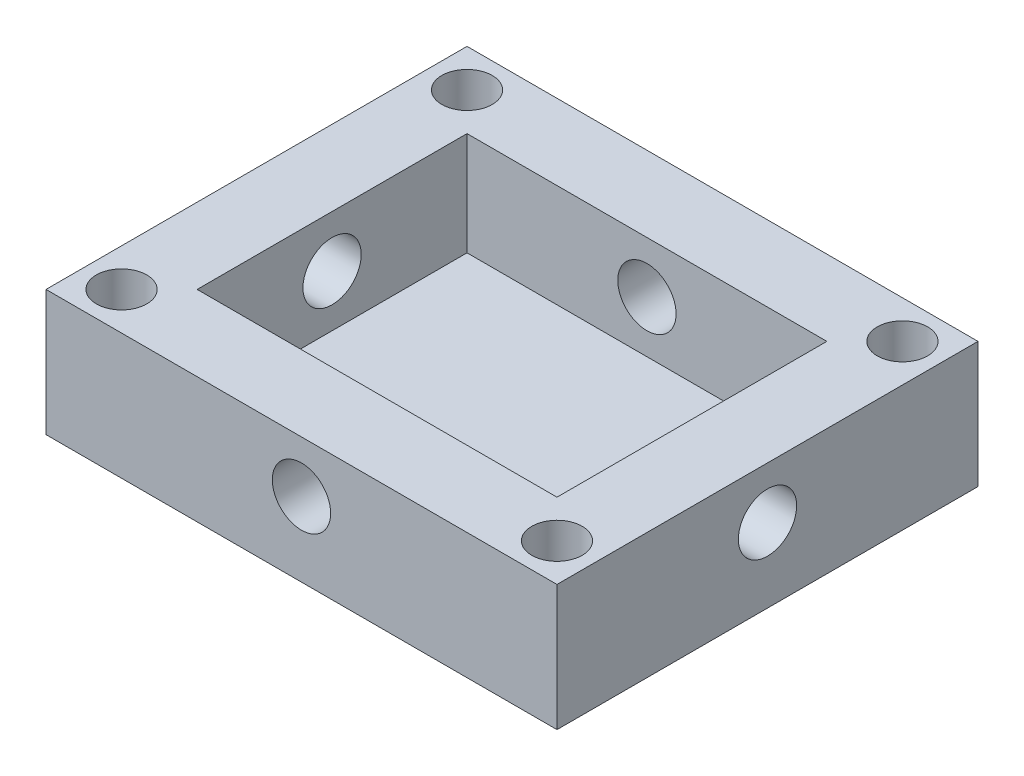
SolidWorks part; units mm, degrees
ref_plane "Front Plane" through (0, 0, 0) normal (0, 0, 1) x (1, 0, 0)
ref_plane "Top Plane" through (0, 0, 0) normal (0, 1, 0) x (1, 0, 0)
ref_plane "Right Plane" through (0, 0, 0) normal (1, 0, 0) x (0, 0, -1)
sketch "Sketch1" plane through (0, 0, 0) normal (0, 1, 0) x (1, 0, 0)
  line L0 (-18.034, 14.859) -> (18.034, 14.859)
  line L1 (-12.7, -9.525) -> (12.7, -9.525)
  line L2 (-12.7, -9.525) -> (-12.7, 9.525)
  line L3 (-12.7, 9.525) -> (12.7, 9.525)
  line L4 (12.7, -9.525) -> (12.7, 9.525)
  line L5 (-12.7, -9.525) -> (12.7, 9.525) construction
  line L6 (-12.7, 9.525) -> (12.7, -9.525) construction
  line L7 (18.034, -14.859) -> (18.034, 14.859)
  line L8 (-18.034, -14.859) -> (18.034, -14.859)
  line L9 (-18.034, -14.859) -> (-18.034, 14.859)
  point P0 (0, 0)
  dimension "D1" = 25.4
  dimension "D2" = 19.05
  dimension "D3" = 5.334
extrude "Boss-Extrude3" add sketch "Sketch1" along normal blind 7.2898
sketch "Sketch4" plane through (0, 0, 0) normal (0, -1, 0) x (1, 0, 0)
  line L1 (-18.034, -14.859) -> (18.034, -14.859)
  line L2 (-18.034, -14.859) -> (-18.034, 14.859)
  line L15 (-18.034, 14.859) -> (18.034, 14.859)
  line L16 (18.034, -14.859) -> (18.034, 14.859)
  line L17 (-18.034, -14.859) -> (18.034, 14.859) construction
  line L18 (-18.034, 14.859) -> (18.034, -14.859) construction
  point P0 (0, 0)
extrude "Boss-Extrude4" add sketch "Sketch4" along normal blind 1.5875
sketch "Sketch5" plane through (0, 7.2898, 0) normal (0, 1, 0) x (1, 0, 0)
  circle A0 centre (-15.367, 12.192) radius 1.778
  circle A1 centre (15.367, 12.192) radius 1.778
  circle A2 centre (15.367, -12.192) radius 1.778
  circle A3 centre (-15.367, -12.192) radius 1.778
extrude "Cut-Extrude2" cut sketch "Sketch5" against normal blind 9.525
sketch "Sketch6" plane through (18.034, 0, 0) normal (1, 0, 0) x (0, 0, -1)
  circle A0 centre (0, 3.6449) radius 2.0574
extrude "Cut-Extrude3" cut sketch "Sketch6" against normal through all and the other way through all
sketch "Sketch7" plane through (0, 0, 14.859) normal (0, 0, 1) x (1, 0, 0)
  circle A0 centre (0, 3.6449) radius 2.0574
extrude "Cut-Extrude4" cut sketch "Sketch7" against normal through all
sketch "Sketch8" plane through (0, 0, 0) normal (0, 1, 0) x (1, 0, 0)
  line L0 (-11.5094, 8.3344) -> (11.5094, 8.3344)
  line L5 (-12.7, -9.525) -> (12.7, 9.525) construction
  line L6 (-12.7, 9.525) -> (12.7, -9.525) construction
  line L7 (11.5094, -8.3344) -> (11.5094, 8.3344)
  line L8 (-11.5094, -8.3344) -> (11.5094, -8.3344)
  line L9 (-11.5094, -8.3344) -> (-11.5094, 8.3344)
  line L11 (-11.5094, 8.3344) -> (11.5094, 8.3344)
  line L12 (-11.5094, 8.3344) -> (-11.5094, -8.3344)
  line L13 (-11.5094, -8.3344) -> (11.5094, -8.3344)
  line L14 (11.5094, 8.3344) -> (11.5094, -8.3344)
  line L15 (-11.5094, 8.3344) -> (11.5094, -8.3344) construction
  line L16 (-11.5094, -8.3344) -> (11.5094, 8.3344) construction
  point P0 (0, 0)
  point P11 (0, 0)
